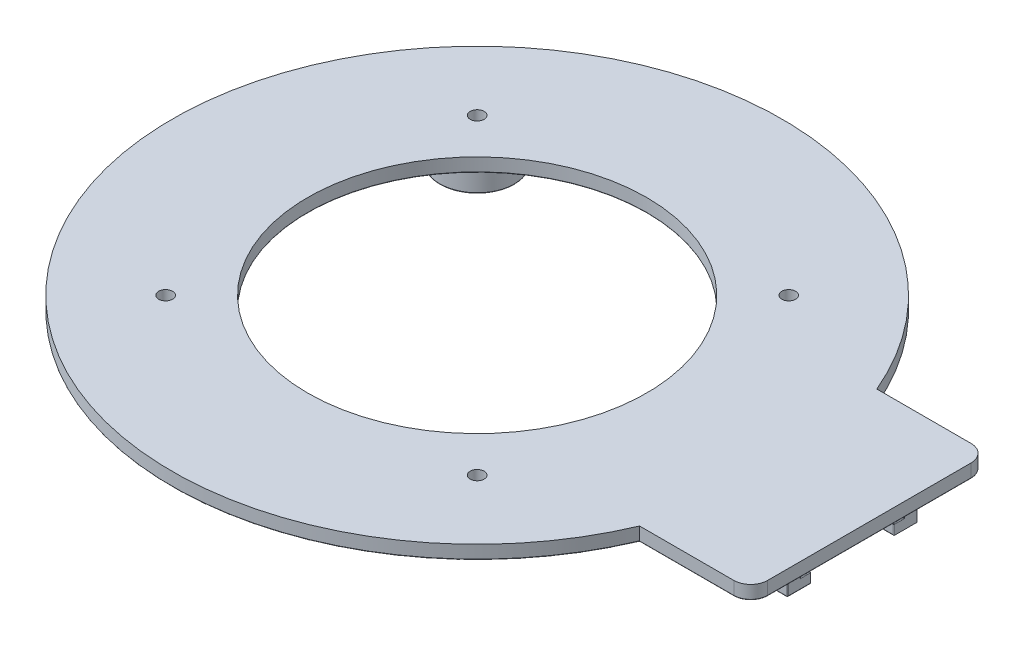
SolidWorks part; units mm, degrees
ref_plane "前视基准面" through (0, 0, 0) normal (0, 0, 1) x (1, 0, 0)
ref_plane "上视基准面" through (0, 0, 0) normal (0, 1, 0) x (1, 0, 0)
ref_plane "右视基准面" through (0, 0, 0) normal (1, 0, 0) x (0, 0, -1)
other "Configuration Table"
sketch "草图1" plane through (0, 0, 0) normal (0, 1, 0) x (1, 0, 0)
  line L0 (35.7071, 35) -> (110.7071, 35)
  line L1 (35.7071, -35) -> (110.7071, -35)
  line L2 (115.7071, 30) -> (115.7071, -30)
  line L3 (0, 0) -> (174.1178, 0) construction
  circle A0 centre (0, 0) radius 50
  circle A1 centre (0, 0) radius 90
  arc A2 (110.7071, 35) -> (115.7071, 30) centre (110.7071, 30) cw
  arc A3 (115.7071, -30) -> (110.7071, -35) centre (110.7071, -30) cw
  point P10 (115.7071, 0)
  dimension "D1" = 100
  dimension "D2" = 180
  dimension "D4" = 5
  dimension "D5" = 5
  dimension "D3" = 80
  dimension "D6" = 70
extrude "凸台-拉伸1" add sketch "草图1" along normal blind 4 contours L0 A1 L1 A0 | A0 L3 A1 L0 | A1 L3 L2 A2 L0 | L3 A1 L1 A3 L2 | L3 A0 L1 A1
ref_plane "基准面1" through (110.7071, 0, 0) normal (1, 0, 0) x (0, 0, -1)
sketch "草图3" plane through (110.7071, 0, 0) normal (1, 0, 0) x (0, 0, -1)
  line L0 (-19.2, 0) -> (-19.2, -8.2)
  line L1 (30, 0) -> (-30, 0) construction
  line L3 (19.2, -8.2) -> (19.2, 0)
  line L4 (19.2, 0) -> (15.2, 0)
  line L5 (15.2, 0) -> (15.2, -5.2)
  line L7 (-15.2, -5.2) -> (-15.2, 0)
  line L8 (-15.2, 0) -> (-19.2, 0)
  line L9 (0, 0) -> (0, 14.2854) construction
  line L10 (-15.2, -5.2) -> (-12.2, -5.2)
  line L11 (-12.2, -5.2) -> (-12.2, -8.2)
  line L12 (-12.2, -8.2) -> (-19.2, -8.2)
  line L13 (19.2, -8.2) -> (12.2, -8.2)
  line L14 (12.2, -8.2) -> (12.2, -5.2)
  line L15 (12.2, -5.2) -> (15.2, -5.2)
  dimension "D1" = 4
  dimension "D2" = 5.2
  dimension "D3" = 30.4
  dimension "D4" = 3
  dimension "D5" = 3
extrude "凸台-拉伸2" add sketch "草图3" against normal blind 30
sketch "草图4" plane through (0, 0, 0) normal (0, -1, 0) x (1, 0, 0)
  line L0 (0, 0) -> (-109.365, 0) construction
  line L1 (-45.9619, 45.9619) -> (45.9619, -45.9619) construction
  line L2 (45.9619, 45.9619) -> (-45.9619, -45.9619) construction
  circle A0 centre (45.9619, -45.9619) radius 2.05
  circle A1 centre (45.9619, 45.9619) radius 2.05
  circle A2 centre (-45.9619, 45.9619) radius 2.05
  circle A3 centre (-45.9619, -45.9619) radius 2.05
  point P7 (0, 0)
  point P8 (0, 0)
  dimension "D4" = 4.1
  dimension "D1" = 45
  dimension "D2" = 45
  dimension "D3" = 130
extrude "切除-拉伸1" cut sketch "草图4" against normal up to next
sketch "草图5" plane through (0, 0, 0) normal (0, -1, 0) x (1, 0, 0)
  circle A0 centre (45.9619, 45.9619) radius 8
  circle A1 centre (45.9619, -45.9619) radius 8
  circle A2 centre (-45.9619, -45.9619) radius 8
  circle A3 centre (-45.9619, 45.9619) radius 8
  dimension "D1" = 16
extrude "拉伸-薄壁1" add sketch "草图5" along normal up to surface (8.2 mm away) thin
fillet "圆角1" radius 0.2 40 edges at (96.8114, 0, -35) (114.2427, 0, 33.5355) (80.7071, -5.2, 13.7) (80.7071, -5.2, -13.7) (0, 0, 50) (80.7071, -2.6, -15.2) (80.7071, -2.6, 15.2) (80.7071, -4.1, -19.2) (80.7071, -6.7, 12.2) (95.7071, -5.2, 12.2) (80.7071, -4.1, 19.2) (95.7071, -5.2, -12.2) (80.7071, -6.7, -12.2) (95.7071, -8.2, -19.2) (95.7071, -8.2, -12.2) (80.7071, -8.2, -15.7) (80.7071, -8.2, 15.7) (45.9619, -8.2, 37.9619) (-45.9619, -8.2, 37.9619) (45.9619, -8.2, -56.9619) (45.9619, -8.2, -53.9619) (-45.9619, -8.2, -53.9619) (-45.9619, -8.2, -56.9619) (-45.9619, -8.2, 34.9619) (45.9619, -8.2, 34.9619) (110.7071, -4.1, 19.2) (95.7071, -8.2, 19.2) (110.7071, -8.2, 15.7) (110.7071, -6.7, 12.2) (110.7071, -2.6, 15.2) (110.7071, -5.2, 13.7) (110.7071, -5.2, -13.7) (110.7071, -6.7, -12.2) (110.7071, -2.6, -15.2) (95.7071, -8.2, 12.2) (110.7071, -4.1, -19.2) (114.2427, 0, -33.5355) (115.7071, 0, 0) (96.8114, 0, 35) (-90, 0, 0)
